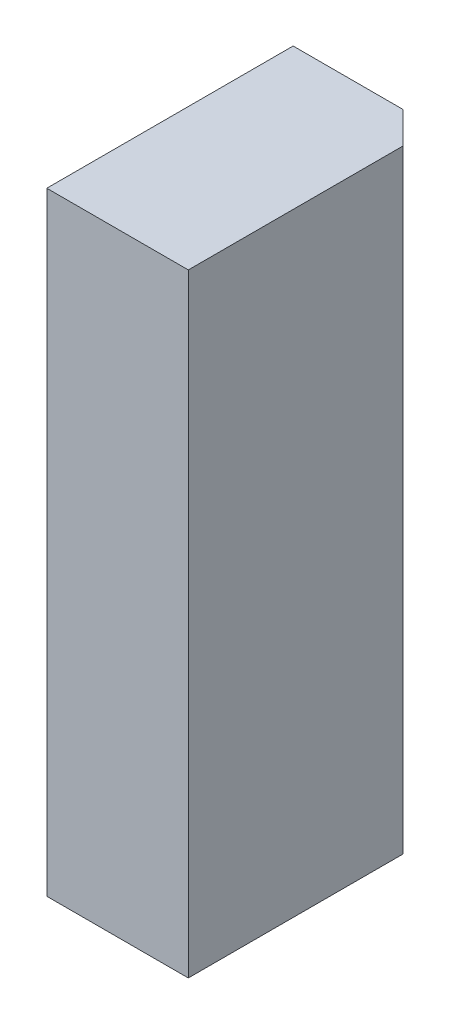
SolidWorks part; units mm, degrees
ref_plane "前基準面" through (0, 0, 0) normal (0, 0, 1) x (1, 0, 0)
ref_plane "上基準面" through (0, 0, 0) normal (0, 1, 0) x (1, 0, 0)
ref_plane "右基準面" through (0, 0, 0) normal (1, 0, 0) x (0, 0, -1)
sketch "草圖1" plane through (0, 0, 0) normal (0, 1, 0) x (1, 0, 0)
  line L1 (-1.35, 2.35) -> (1.35, 2.35)
  line L2 (-1.35, 2.35) -> (-1.35, -2.35)
  line L3 (-1.35, -2.35) -> (1.35, -2.35)
  line L4 (1.35, 2.35) -> (1.35, -2.35)
  line L5 (-1.35, 2.35) -> (1.35, -2.35) construction
  line L6 (-1.35, -2.35) -> (1.35, 2.35) construction
  point P0 (0, 0)
  dimension "D1" = 2.7
  dimension "D2" = 4.7
extrude "伸長1" add sketch "草圖1" along normal blind 11.7
chamfer "導角1" distance 0.6 angle 45 1 edges at (1.35, 5.85, -2.35)
sketch "草圖3" plane through (-1.35, 0, 0) normal (-1, 0, 0) x (0, 0, 1)
  line L0 (-2.45, 0) -> (-2.45, 1) construction
  line L1 (-2.35, 0) -> (2.35, 0) construction
  line L2 (2.35, 11.7) -> (2.35, 0) construction
  circle A0 centre (-2.45, 1) radius 0.5
  dimension "D2" = 1
  dimension "D1" = 4.8
  dimension "D3" = 1
extrude "伸長2" cut sketch "草圖3" against normal up to next
